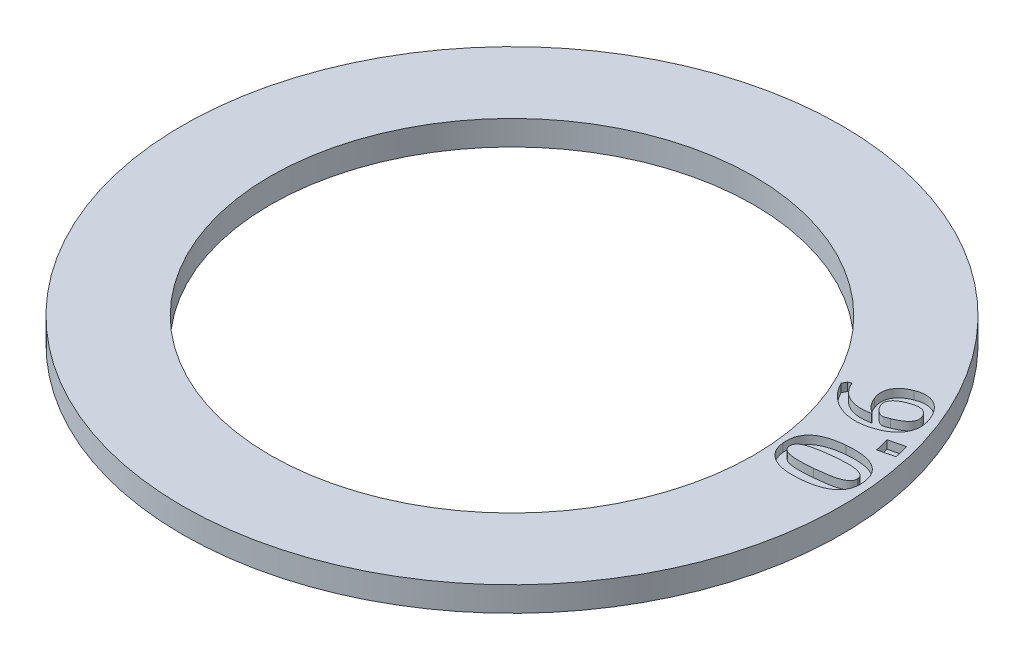
SolidWorks part; units mm, degrees
ref_plane "Front Plane" through (0, 0, 0) normal (0, 0, 1) x (1, 0, 0)
ref_plane "Top Plane" through (0, 0, 0) normal (0, 1, 0) x (1, 0, 0)
ref_plane "Right Plane" through (0, 0, 0) normal (1, 0, 0) x (0, 0, -1)
sketch "Sketch1" plane through (0, 0, 0) normal (0, 1, 0) x (1, 0, 0)
  circle A0 centre (0, 0) radius 8.001
  dimension "D1" = 16.002
extrude "Boss-Extrude1" add sketch "Sketch1" along normal blind 0.6
sketch "Sketch2" plane through (0, 0, 0) normal (0, -1, 0) x (-1, 0, 0)
  circle A0 centre (0, 0) radius 5.8674
  dimension "D1" = 11.7348
extrude "Cut-Extrude1" cut sketch "Sketch2" against normal through all
sketch "Sketch4" plane through (0, 0.6, 0) normal (0, 1, 0) x (1, 0, 0)
  circle A0 centre (0, 0) radius 7.8193 construction
  text T0 "<b>0.6</b>" font "Cambria" height 1.778
extrude "Cut-Extrude2" cut sketch "Sketch4" against normal blind 0.2
